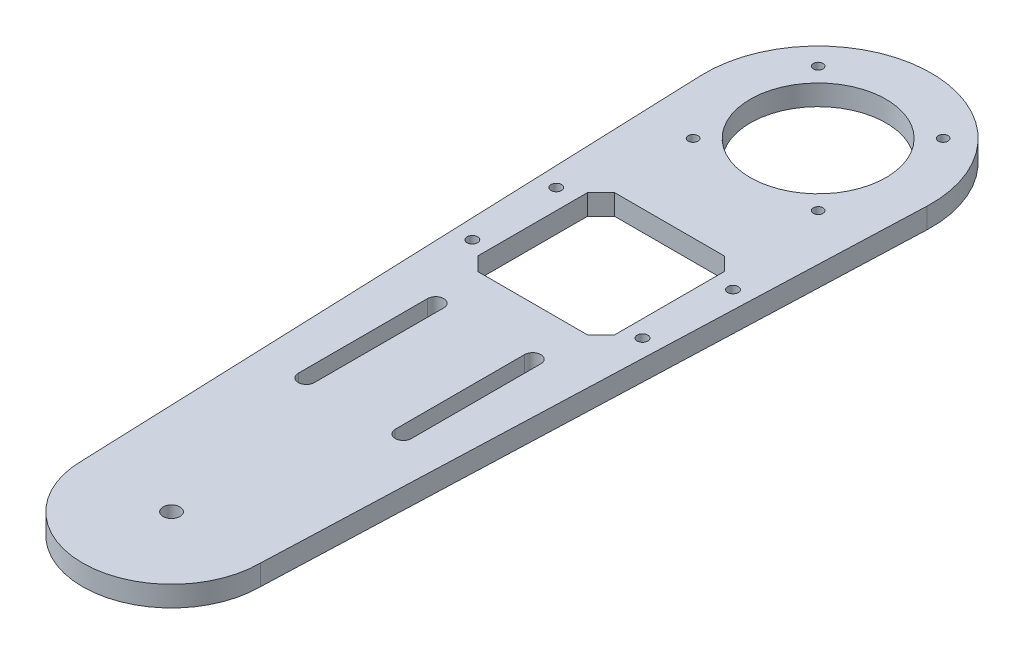
SolidWorks part; units mm, degrees
ref_plane "Front Plane" through (0, 0, 0) normal (0, 0, 1) x (1, 0, 0)
ref_plane "Top Plane" through (0, 0, 0) normal (0, 1, 0) x (1, 0, 0)
ref_plane "Right Plane" through (0, 0, 0) normal (1, 0, 0) x (0, 0, -1)
sketch "Sketch1" plane through (0, 0, 0) normal (0, 1, 0) x (1, 0, 0)
  line L0 (27.5, 0) -> (34.9753, 198.6841)
  line L1 (-27.5, 0) -> (-34.9753, 198.6841)
  arc A0 (-27.5, 0) -> (27.5, 0) centre (0, 0) ccw
  arc A3 (34.9753, 198.6841) -> (-34.9753, 198.6841) centre (0, 200) ccw
  dimension "D1" = 55
  dimension "D3" = 200
  dimension "D2" = 70
extrude "Boss-Extrude1" add sketch "Sketch1" along normal blind 6.35
sketch "Sketch2" plane through (0, 6.35, 0) normal (0, 1, 0) x (1, 0, 0)
  circle A0 centre (0, 0) radius 2.6
  dimension "D1" = 5.2
extrude "Cut-Extrude1" cut sketch "Sketch2" against normal through all
sketch "Esquisse4" plane through (0, 6.35, 0) normal (0, 1, 0) x (1, 0, 0)
  circle A0 centre (0, 200) radius 35
  arc A1 (34.9753, 198.6841) -> (-34.9753, 198.6841) centre (0, 200) ccw construction
sketch "Esquisse3" plane through (0, 6.35, 0) normal (0, 1, 0) x (1, 0, 0)
  circle A1 centre (0, 200) radius 21
  dimension "D1" = 42
extrude "Enlèv. mat.-Extru.2" cut sketch "Esquisse3" against normal through all
sketch "Esquisse5" plane through (0, 6.35, 0) normal (0, 1, 0) x (1, 0, 0)
  circle A0 centre (0, 200) radius 27.35
  dimension "D1" = 54.7
sketch "Esquisse7" plane through (0, 6.35, 0) normal (0, 1, 0) x (1, 0, 0)
  line L0 (-19.3394, 180.6606) -> (19.3394, 180.6606) construction
  line L1 (19.3394, 180.6606) -> (19.3394, 219.3394) construction
  line L2 (19.3394, 219.3394) -> (-19.3394, 219.3394) construction
  line L3 (-19.3394, 219.3394) -> (-19.3394, 180.6606) construction
  circle A0 centre (-19.3394, 219.3394) radius 1.5
  circle A2 centre (19.3394, 219.3394) radius 1.5
  circle A3 centre (19.3394, 180.6606) radius 1.5
  circle A4 centre (-19.3394, 180.6606) radius 1.5
  circle A5 centre (0, 200) radius 27.35 construction
  point P2 (0, 180.6606)
  dimension "D1" = 3
extrude "Enlèv. mat.-Extru.3" cut sketch "Esquisse7" against normal through all
sketch "Sketch3" plane through (0, 6.35, 0) normal (0, 1, 0) x (1, 0, 0)
  line L0 (21.15, 149.8281) -> (21.15, 115.8719)
  line L1 (21.15, 115.8719) -> (16.9781, 111.7)
  line L2 (16.9781, 111.7) -> (-16.9781, 111.7)
  line L3 (-16.9781, 111.7) -> (-21.15, 115.8719)
  line L5 (-21.15, 149.8281) -> (-16.9781, 154)
  line L6 (-16.9781, 154) -> (16.9781, 154)
  line L7 (16.9781, 154) -> (21.15, 149.8281)
  line L8 (-33.3624, 132.85) -> (44.6173, 132.85) construction
  line L9 (0, 172.7946) -> (0, 110.3908) construction
  line L10 (-21.15, 115.8719) -> (-21.15, 149.8281)
  circle A0 centre (0, 200) radius 21 construction
  point P12 (0, 154)
  point P13 (0, 111.7)
  point P14 (21.15, 132.85)
  point P21 (0, 141.5927)
  dimension "D1" = 46
  dimension "D2" = 5.9
  dimension "D3" = 33.9561
  dimension "D5" = 42.3
extrude "Cut-Extrude2" cut sketch "Sketch3" against normal through all
sketch "Sketch5" plane through (0, 6.35, 0) normal (0, 1, 0) x (1, 0, 0)
  line L0 (-27.3317, 146.3405) -> (-26.3166, 119.3595) construction
  line L2 (-27.5, 0) -> (-34.9753, 198.6841) construction
  line L3 (-21.15, 149.8281) -> (-21.15, 115.8719) construction
  line L4 (-27.3317, 146.3405) -> (-33.0059, 146.3405) construction
  line L5 (-33.0059, 146.3405) -> (-31.9908, 119.3595) construction
  line L6 (-31.9908, 119.3595) -> (-26.3166, 119.3595) construction
  line L7 (-32.4983, 132.85) -> (-21.15, 132.85) construction
  circle A2 centre (-27.3317, 146.3405) radius 1.625
  circle A3 centre (-26.3166, 119.3595) radius 1.625
  point P8 (-21.15, 132.85)
  point P9 (-26.8242, 132.85)
  point P12 (-26.8242, 132.85)
  dimension "D1" = 3.25
  dimension "D2" = 27
extrude "Cut-Extrude3" cut sketch "Sketch5" against normal through all
mirror "Mirror1" about plane through (0, 0, 0) normal (1, 0, 0) of "Cut-Extrude3"
sketch "Sketch8" plane through (0, 6.35, 0) normal (0, 1, 0) x (1, 0, 0)
  line L0 (-15, 96.7) -> (-15, 56.7) construction
  line L1 (-12.5, 96.7) -> (-12.5, 56.7)
  line L2 (-17.5, 96.7) -> (-17.5, 56.7)
  line L3 (-16.9781, 111.7) -> (16.9781, 111.7) construction
  arc A0 (-12.5, 96.7) -> (-17.5, 96.7) centre (-15, 96.7) ccw
  arc A1 (-17.5, 56.7) -> (-12.5, 56.7) centre (-15, 56.7) ccw
  point P2 (-15, 76.7)
  dimension "D3" = 2.5
  dimension "D1" = 40
  dimension "D2" = 35
  dimension "D4" = 15
extrude "Cut-Extrude5" cut sketch "Sketch8" against normal through all
mirror "Mirror2" about plane through (0, 0, 0) normal (1, 0, 0) of "Cut-Extrude5"
